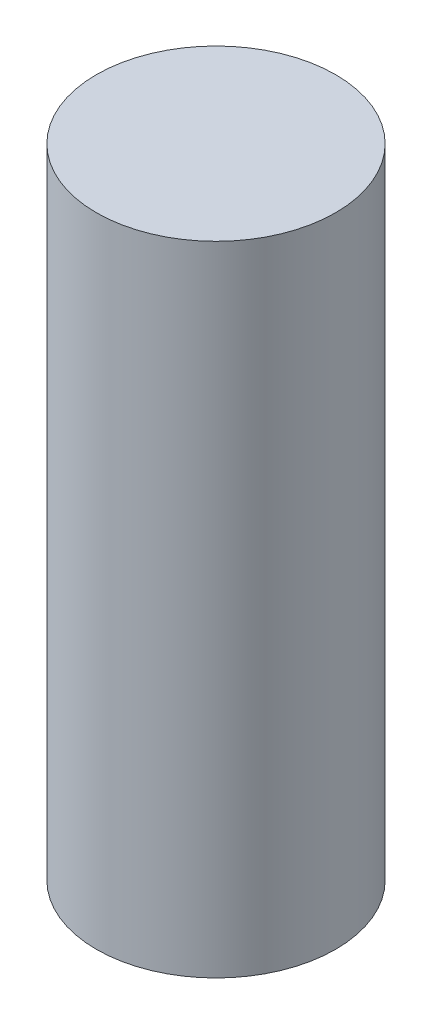
SolidWorks part; units mm, degrees
ref_plane "Front Plane" through (0, 0, 0) normal (0, 0, 1) x (1, 0, 0)
ref_plane "Top Plane" through (0, 0, 0) normal (0, 1, 0) x (1, 0, 0)
ref_plane "Right Plane" through (0, 0, 0) normal (1, 0, 0) x (0, 0, -1)
sketch "Sketch1" plane through (0, 0, 0) normal (0, 1, 0) x (1, 0, 0)
  circle A0 centre (0, 0) radius 2.25
  dimension "D1" = 4.5
extrude "Boss-Extrude1" add sketch "Sketch1" along normal blind 12
scale "Scale1" scale about centroid uniform scaling yes scale factor 0.8
